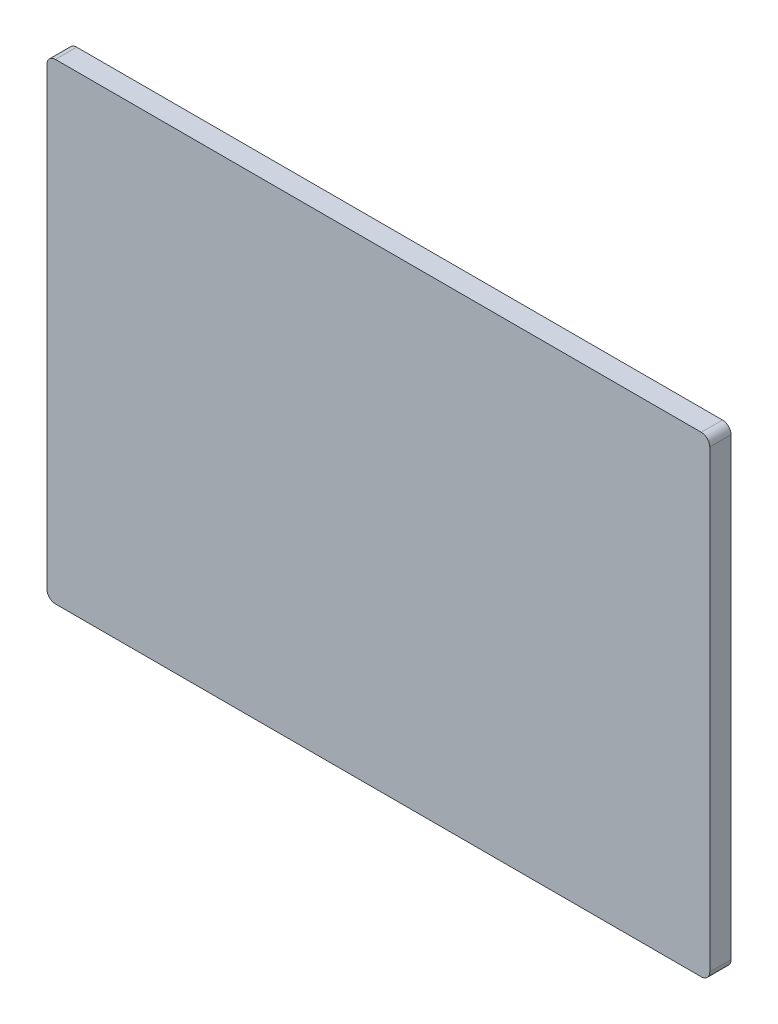
SolidWorks part; units mm, degrees
ref_plane "Front Plane" through (0, 0, 0) normal (0, 0, 1) x (1, 0, 0)
ref_plane "Top Plane" through (0, 0, 0) normal (0, 1, 0) x (1, 0, 0)
ref_plane "Right Plane" through (0, 0, 0) normal (1, 0, 0) x (0, 0, -1)
sketch "Sketch1" plane through (0, 0, 0) normal (0, 0, 1) x (1, 0, 0)
  line L1 (75, -52.5) -> (-75, -52.5) construction
  line L2 (75, -52.5) -> (75, 52.5) construction
  line L3 (75, 52.5) -> (-75, 52.5) construction
  line L4 (-75, -52.5) -> (-75, 52.5) construction
  line L5 (75, -52.5) -> (-75, 52.5) construction
  line L6 (75, 52.5) -> (-75, -52.5) construction
  point P0 (0, 0)
  dimension "D1" = 150
  dimension "D2" = 105
sketch "Sketch2" plane through (0, 0, 0) normal (0, 0, 1) x (1, 0, 0)
  line L0 (75, 52.5) -> (-75, 52.5) construction
  line L1 (78, -55.5) -> (-78, -55.5)
  line L2 (78, -55.5) -> (78, 55.5)
  line L3 (78, 55.5) -> (-78, 55.5)
  line L4 (-78, -55.5) -> (-78, 55.5)
  line L5 (78, -55.5) -> (-78, 55.5) construction
  line L6 (78, 55.5) -> (-78, -55.5) construction
  line L7 (75, -52.5) -> (75, 52.5) construction
  point P0 (0, 0)
  dimension "D1" = 3
  dimension "D2" = 3
extrude "Boss-Extrude1" add sketch "Sketch2" along normal blind 5
fillet "Fillet1" radius 2 4 edges at (-78, -55.5, 2.5) (78, -55.5, 2.5) (78, 55.5, 2.5) (-78, 55.5, 2.5)
